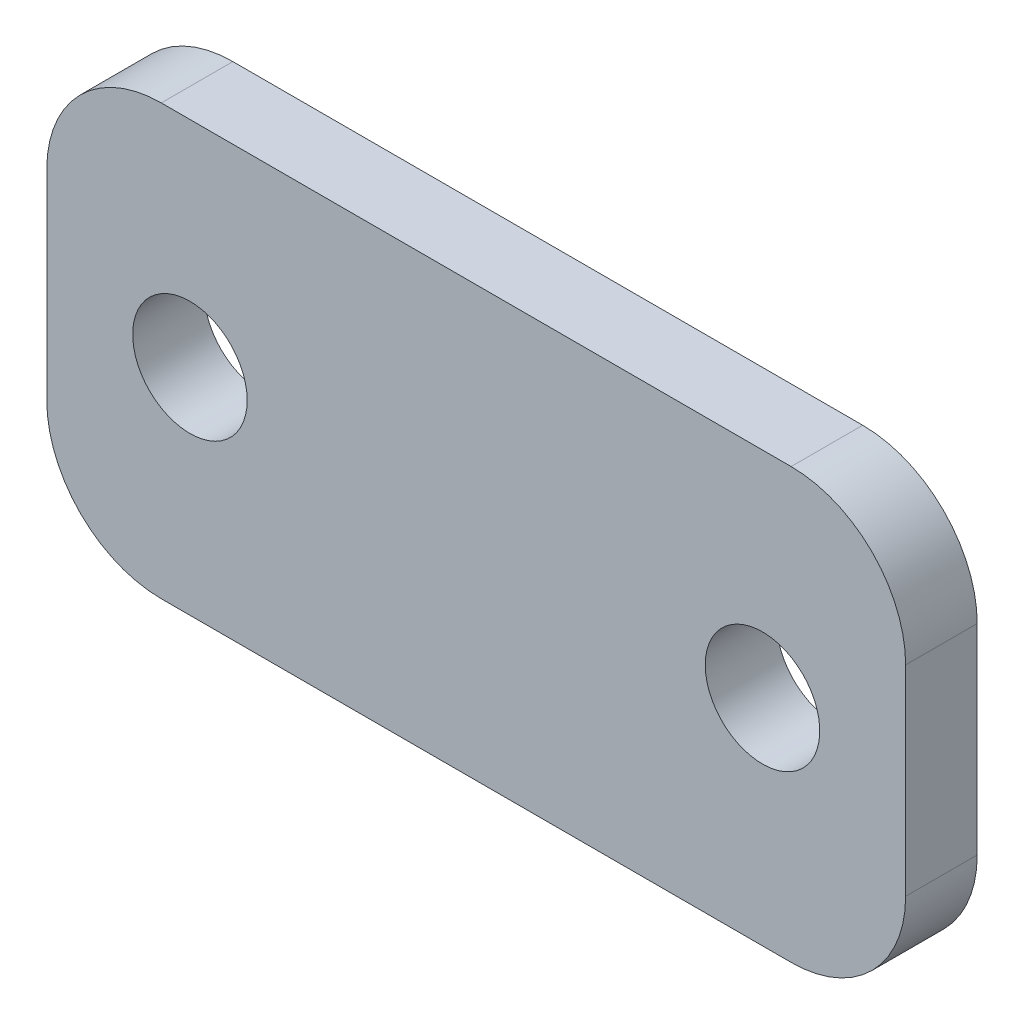
SolidWorks part; units mm, degrees
ref_plane "Front Plane" through (0, 0, 0) normal (0, 0, 1) x (1, 0, 0)
ref_plane "Top Plane" through (0, 0, 0) normal (0, 1, 0) x (1, 0, 0)
ref_plane "Right Plane" through (0, 0, 0) normal (1, 0, 0) x (0, 0, -1)
sketch "Sketch1" plane through (0, 0, 0) normal (0, 0, 1) x (1, 0, 0)
  line L1 (22, -15) -> (-22, -15)
  line L2 (30, -7) -> (30, 7)
  line L3 (22, 15) -> (-22, 15)
  line L4 (-30, -7) -> (-30, 7)
  arc A0 (-22, -15) -> (-30, -7) centre (-22, -7) cw
  arc A1 (-22, 15) -> (-30, 7) centre (-22, 7) ccw
  arc A2 (22, -15) -> (30, -7) centre (22, -7) ccw
  arc A3 (30, 7) -> (22, 15) centre (22, 7) ccw
  circle A4 centre (-20, 0) radius 4
  circle A5 centre (20, 0) radius 4
  point P0 (0, 0)
  point P1 (0, 0)
  point P23 (0, 0)
  dimension "D3" = 8
  dimension "D4" = 8
  dimension "D6" = 8
  dimension "D5" = 40
extrude "Boss-Extrude1" add sketch "Sketch1" along normal blind 5
sketch "Sketch4" plane through (0, 0, 0) normal (1, 0, 0) x (0, 0, -1)
  line L0 (-5, 15) -> (-34.2421, 7.1646)
  line L1 (-5, 15) -> (-36.2535, 15) construction
  line L2 (-5, -15) -> (-26.2798, -15)
  line L3 (-20.3689, -15) -> (-27.7716, -16.9835)
  arc A0 (-34.2421, 7.1646) -> (-27.7716, -16.9835) centre (-31.0069, -4.9095) ccw
  circle A1 centre (-31.0069, -4.9095) radius 4
  dimension "D2" = 12.5
  dimension "D3" = 8
  dimension "D1" = 15
